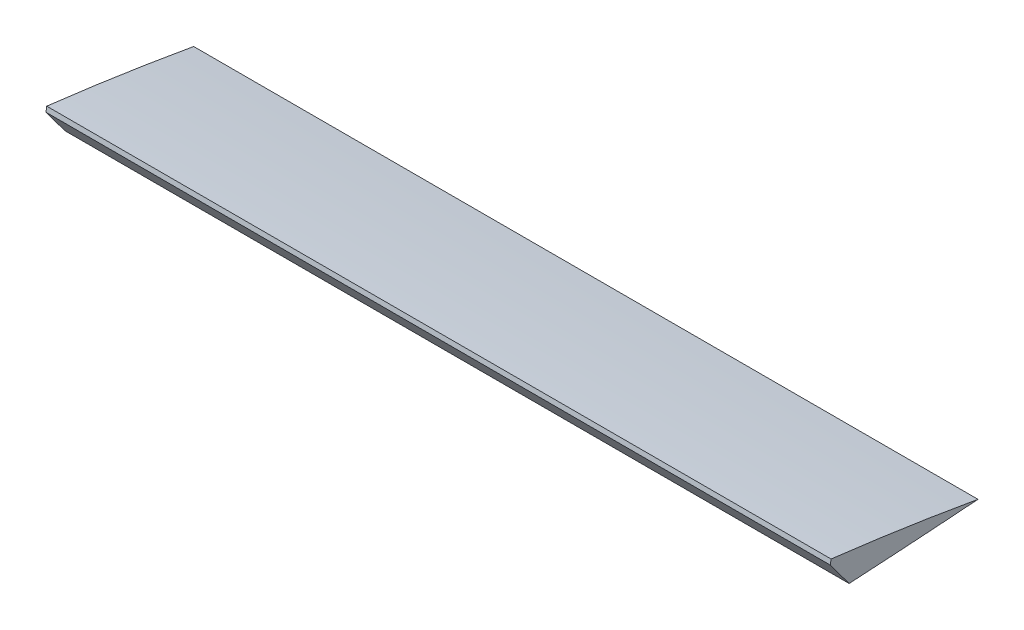
SolidWorks part; units mm, degrees
material "EPS 1.5lb"
ref_plane "Front Plane" through (0, 0, 0) normal (0, 0, 1) x (1, 0, 0)
ref_plane "Top Plane" through (0, 0, 0) normal (0, 1, 0) x (1, 0, 0)
ref_plane "Right Plane" through (0, 0, 0) normal (1, 0, 0) x (0, 0, -1)
sketch "Sketch1" plane through (0, 0, -687.8616) normal (-1, 0, 0) x (0, 0, 1)
  line L0 (687.8616, 0) -> (690.0965, -15.0629)
  line L1 (687.8616, 0) -> (677.2218, -14.347) construction
  arc A0 (617.6716, -10.4138) -> (687.8616, 0) centre (835.3626, -1235.9198) cw
  arc A1 (617.6716, -10.4138) -> (690.0965, -15.0629) centre (877.2773, 3467.3522) ccw
  dimension "D1" = 1244.6904
  dimension "D2" = 3487.442
  dimension "D3" = 70.19
  dimension "D4" = 15.0629
  dimension "D5" = 45
  dimension "D6" = 72.4249
  dimension "D7" = 10.4138
extrude "Boss-Extrude1" add sketch "Sketch1" along normal mid plane 374.65 separate body
sketch "Sketch2" plane through (0, 0, 0) normal (1, 0, 0) x (0, 0, -1)
  line L0 (-2.2348, -15.0629) -> (0, 0)
  line L1 (-2.2348, -15.0629) -> (0, 0) construction
  line L2 (-0.3495, -2.3555) -> (8.6288, -14.462)
  line L3 (-0.3495, -2.3555) -> (-2.2348, -15.0629)
  arc A0 (70.19, -10.4138) -> (0, 0) centre (-147.5009, -1235.9198) ccw
  arc A1 (70.19, -10.4138) -> (0, 0) centre (-147.5009, -1235.9198) ccw construction
  arc A2 (-2.2348, -15.0629) -> (70.19, -10.4138) centre (-189.4157, 3467.3522) ccw
  arc A3 (-2.2348, -15.0629) -> (70.19, -10.4138) centre (-189.4157, 3467.3522) ccw construction
  arc A4 (-2.2348, -15.0629) -> (8.6288, -14.462) centre (-189.4157, 3467.3522) ccw
  dimension "D1" = 45
  dimension "D2" = 2.3813
extrude "Cut-Extrude1" cut sketch "Sketch2" against normal through all and the other way through all
move or copy body "Body-Move/Copy1" [suppressed] bodies to move or copy 103
